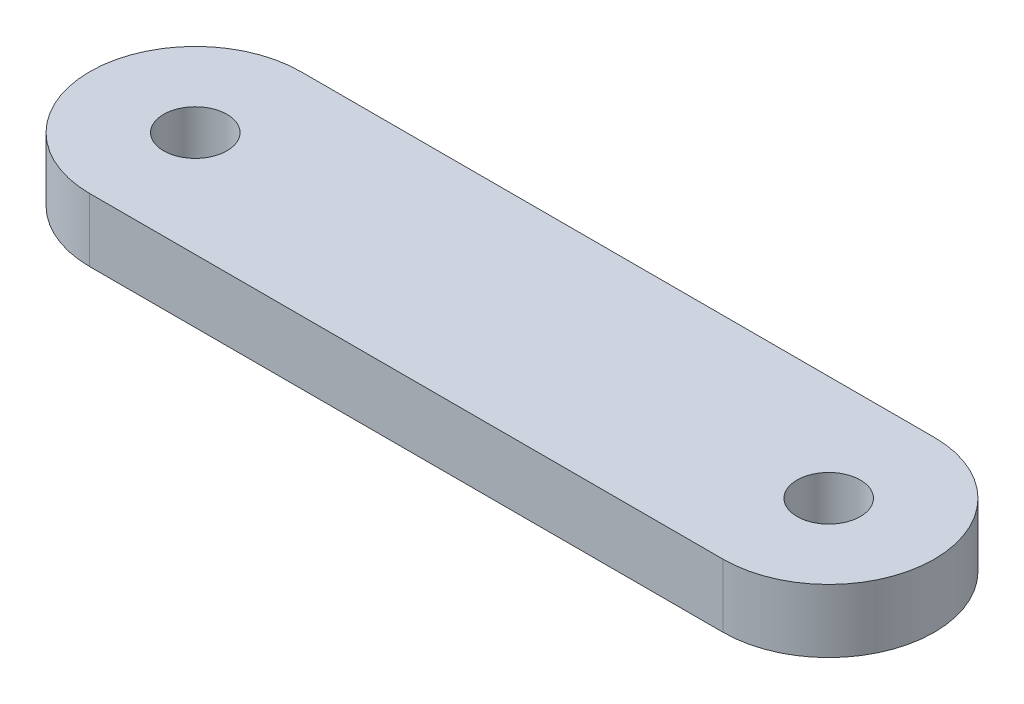
SolidWorks part; units mm, degrees
ref_plane "前视基准面" through (0, 0, 0) normal (0, 0, 1) x (1, 0, 0)
ref_plane "上视基准面" through (0, 0, 0) normal (0, 1, 0) x (1, 0, 0)
ref_plane "右视基准面" through (0, 0, 0) normal (1, 0, 0) x (0, 0, -1)
sketch "草图1" plane through (0, 0, 0) normal (0, 1, 0) x (1, 0, 0)
  line L0 (-15, 0) -> (15, 0) construction
  line L1 (-15, 5) -> (15, 5)
  line L2 (-15, -5) -> (15, -5)
  arc A0 (-15, 5) -> (-15, -5) centre (-15, 0) ccw
  arc A1 (15, -5) -> (15, 5) centre (15, 0) ccw
  point P3 (0, 0)
  dimension "D1" = 30
  dimension "D2" = 5
  dimension "D3" = 0
extrude "凸台-拉伸1" add sketch "草图1" along normal blind 3
sketch "草图2" plane through (0, 3, 0) normal (0, 1, 0) x (1, 0, 0)
  circle A0 centre (-15, 0) radius 1.5
  circle A1 centre (15, 0) radius 1.5
  dimension "D1" = 3
  dimension "D3" = 3
  dimension "D2" = 15
  dimension "D4" = 15
extrude "切除-拉伸1" cut sketch "草图2" against normal blind 10
